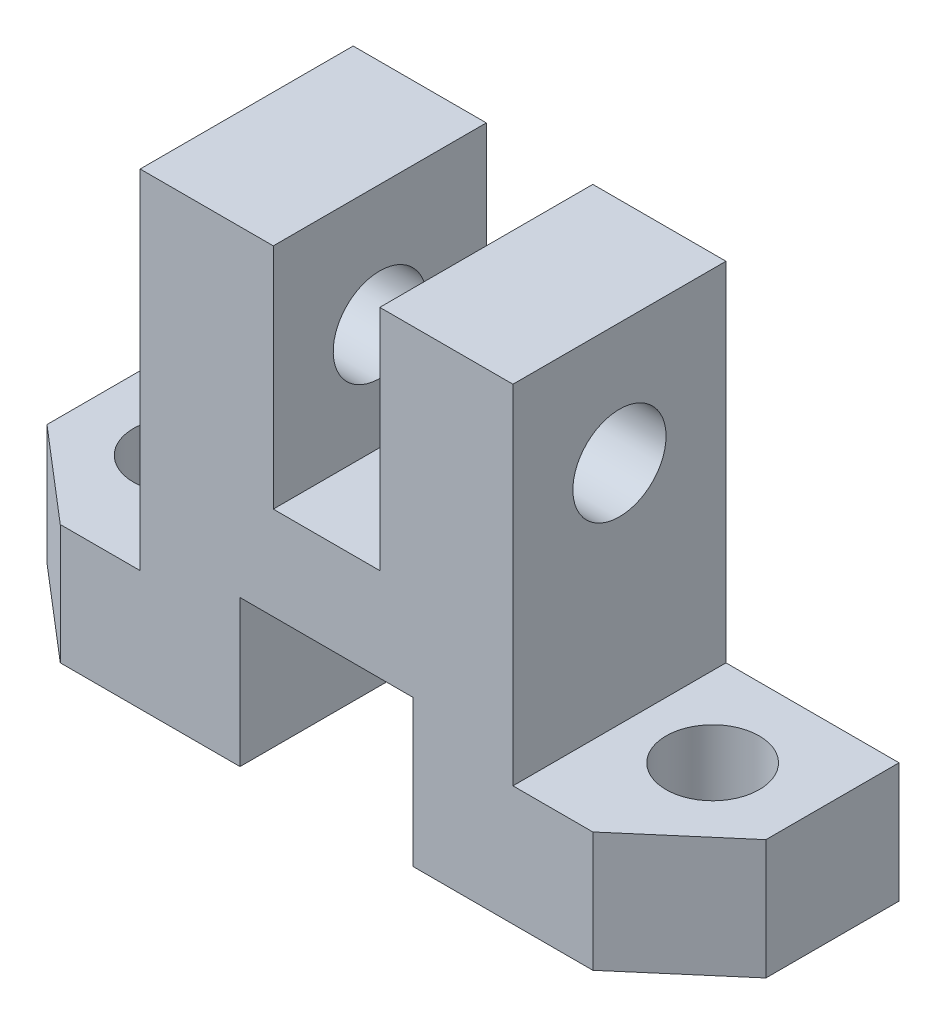
SolidWorks part; units mm, degrees
ref_plane "Alzado" through (0, 0, 0) normal (0, 0, 1) x (1, 0, 0)
ref_plane "Planta" through (0, 0, 0) normal (0, 1, 0) x (1, 0, 0)
ref_plane "Vista lateral" through (0, 0, 0) normal (1, 0, 0) x (0, 0, -1)
sketch "Croquis2" plane through (0, 0, 0) normal (0, 1, 0) x (1, 0, 0)
  line L0 (-27, 7) -> (-27, -3)
  line L1 (-27, -3) -> (-20, -9)
  line L2 (-20, -9) -> (-6.5, -9)
  line L3 (-6.5, -9) -> (-6.5, 7)
  line L4 (-6.5, 7) -> (-27, 7)
  line L5 (0, 0) -> (0, -5.5566) construction
  line L6 (6.5, 7) -> (27, 7)
  line L7 (6.5, -9) -> (6.5, 7)
  line L8 (20, -9) -> (6.5, -9)
  line L9 (27, -3) -> (20, -9)
  line L10 (27, 7) -> (27, -3)
  circle A0 centre (-20, 0) radius 3.5
  circle A1 centre (20, 0) radius 3.5
  dimension "D7" = 7
  dimension "D1" = 7
  dimension "D2" = 27
  dimension "D3" = 10
  dimension "D4" = 16
  dimension "D5" = 20
  dimension "D6" = 6.5
  dimension "D8" = 7
  dimension "D9" = 7
extrude "Saliente-Extruir1" add sketch "Croquis2" along normal blind 9
sketch "Croquis3" plane through (0, 0, 9) normal (0, 0, 1) x (1, 0, 0)
  line L0 (6.5, 9) -> (6.5, 11)
  line L1 (6.5, 11) -> (-6.5, 11)
  line L2 (14, 9) -> (14, 35.1241)
  line L3 (6.5, 9) -> (20, 9) construction
  line L4 (14, 35.1241) -> (4, 35.1241)
  line L5 (4, 35.1241) -> (4, 18)
  line L6 (4, 18) -> (-4, 18)
  line L7 (27, 9) -> (27, 0) construction
  line L8 (0, 18) -> (0, 11) construction
  line L9 (-4, 35.1241) -> (-4, 18)
  line L10 (-14, 35.1241) -> (-4, 35.1241)
  line L11 (-14, 9) -> (-14, 35.1241)
  line L12 (-6.5, 9) -> (-6.5, 11)
  line L13 (-14, 9) -> (-6.5, 9)
  line L14 (6.5, 9) -> (14, 9)
  dimension "D1" = 13
  dimension "D2" = 7
  dimension "D3" = 10
  dimension "D4" = 11
extrude "Saliente-Extruir2" add sketch "Croquis3" against normal blind 16
sketch "Croquis4" plane through (14, 0, 0) normal (1, 0, 0) x (0, 0, -1)
  line L1 (-3, 0) -> (7, 0) construction
  line L3 (7, 9) -> (7, 35.1241) construction
  circle A0 centre (-1, 26) radius 3.5
  dimension "D1" = 7
  dimension "D2" = 26
  dimension "D3" = 8
extrude "Cortar-Extruir1" cut sketch "Croquis4" against normal blind 28
